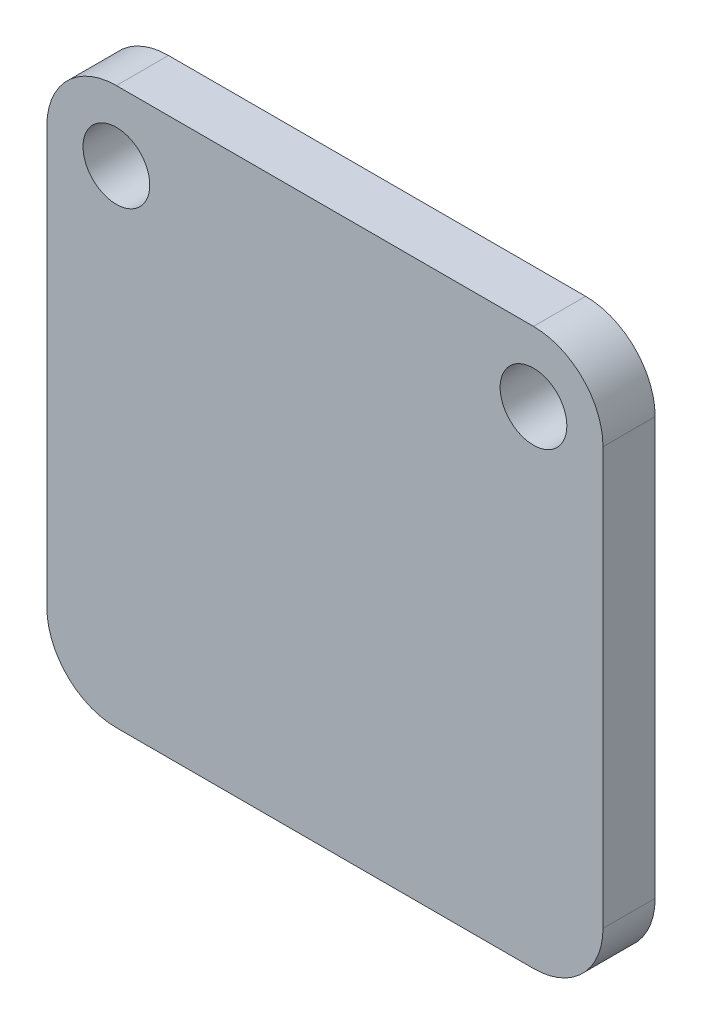
SolidWorks part; units mm, degrees
ref_plane "Front Plane" through (0, 0, 0) normal (0, 0, 1) x (1, 0, 0)
ref_plane "Top Plane" through (0, 0, 0) normal (0, 1, 0) x (1, 0, 0)
ref_plane "Right Plane" through (0, 0, 0) normal (1, 0, 0) x (0, 0, -1)
sketch "Sketch1" plane through (0, 0, 0) normal (0, 0, 1) x (1, 0, 0)
  line L1 (10.16, -10.16) -> (-10.16, -10.16)
  line L2 (10.16, -10.16) -> (10.16, 10.16)
  line L3 (10.16, 10.16) -> (-10.16, 10.16)
  line L4 (-10.16, -10.16) -> (-10.16, 10.16)
  line L5 (10.16, -10.16) -> (-10.16, 10.16) construction
  line L6 (10.16, 10.16) -> (-10.16, -10.16) construction
  point P0 (0, 0)
  dimension "D1" = 20.32
  dimension "D2" = 20.32
extrude "Boss-Extrude1" add sketch "Sketch1" along normal blind 1.905
sketch "Sketch2" plane through (0, 0, 1.905) normal (0, 0, 1) x (1, 0, 0)
  line L0 (10.16, 10.16) -> (-10.16, 10.16) construction
  circle A0 centre (-7.62, 7.62) radius 1.2192
  circle A1 centre (7.62, 7.62) radius 1.2192
  point P7 (0, 0)
  dimension "D4" = 2.4384
  dimension "D1" = 15.24
  dimension "D2" = 7.62
  dimension "D3" = 2.54
extrude "Cut-Extrude1" cut sketch "Sketch2" against normal up to next
fillet "Fillet1" radius 2.54 4 edges at (-10.16, -10.16, 0.9525) (10.16, -10.16, 0.9525) (-10.16, 10.16, 0.9525) (10.16, 10.16, 0.9525)
sketch "Sketch3" plane through (0, 0, 1.905) normal (0, 0, 1) x (1, 0, 0)
  line L0 (-10.16, 7.62) -> (-10.16, -7.62) construction
  line L1 (-10.16, -4.9768) -> (10.16, -4.9768) construction
  line L2 (-10.16, -4.9768) -> (-10.16, -10.16) construction
  line L3 (-10.16, -10.16) -> (10.16, -10.16) construction
  line L4 (10.16, -4.9768) -> (10.16, -10.16) construction
  line L5 (-7.62, -10.16) -> (7.62, -10.16) construction
  line L6 (10.16, -7.62) -> (10.16, 7.62) construction
  dimension "D1" = 5.1832
equation "\"D2@Sketch2\"=\"D1@Sketch2\"/2"
